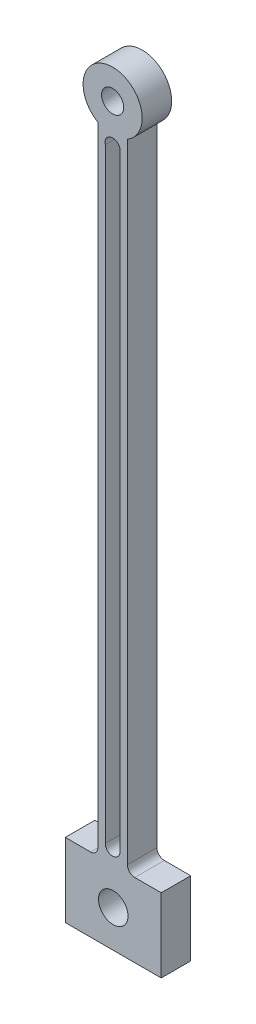
SolidWorks part; units mm, degrees
ref_plane "Front Plane" through (0, 0, 0) normal (0, 0, 1) x (1, 0, 0)
ref_plane "Top Plane" through (0, 0, 0) normal (0, 1, 0) x (1, 0, 0)
ref_plane "Right Plane" through (0, 0, 0) normal (1, 0, 0) x (0, 0, -1)
sketch "Sketch1" plane through (0, 0, 0) normal (0, 0, 1) x (1, 0, 0)
  line L0 (-6, -179.1632) -> (-12.837, -179.1632)
  line L2 (4, -6.9282) -> (4, -177.1632)
  line L4 (-4, -6.9282) -> (-4, -177.1632)
  line L5 (13.163, -179.1632) -> (6, -179.1632)
  line L6 (13.163, -179.1632) -> (13.163, -199.1632)
  line L7 (13.163, -199.1632) -> (-12.837, -199.1632)
  line L8 (-12.837, -179.1632) -> (-12.837, -199.1632)
  line L9 (13.163, -179.1632) -> (-12.837, -199.1632) construction
  line L10 (13.163, -199.1632) -> (-12.837, -179.1632) construction
  line L13 (-2, -11.1769) -> (-2, -175.1632)
  line L15 (2, -11.1769) -> (2, -175.1632)
  arc A0 (4, -6.9282) -> (-4, -6.9282) centre (0, 0) ccw
  circle A1 centre (0, 0) radius 5
  circle A2 centre (0, 0) radius 3
  circle A3 centre (0.163, -189.1632) radius 4
  circle A4 centre (0.163, -189.1632) radius 6
  arc A5 (-6, -179.1632) -> (-4, -177.1632) centre (-6, -177.1632) ccw
  arc A6 (6, -179.1632) -> (4, -177.1632) centre (6, -177.1632) cw
  arc A7 (2, -11.1769) -> (-2, -11.1769) centre (0, -10.6821) ccw
  arc A8 (-2, -175.1632) -> (2, -175.1632) centre (0, -175.1632) ccw
  point P17 (-4, -179.1632)
  point P28 (0, -177.1632)
  dimension "D1" = 16
  dimension "D2" = 10
  dimension "D3" = 6
  dimension "D5" = 26
  dimension "D7" = 12
  dimension "D8" = 8
  dimension "D4" = 2
  dimension "D12" = 166.4811
  dimension "D6" = 20
  dimension "D9" = 2
  dimension "D10" = 4
  dimension "D11" = 2
  dimension "D13" = 4
extrude "Boss-Extrude1" add sketch "Sketch1" along normal blind 8 contours L5 A6 L2 A0 L4 A5 L0 L8 L7 L6 A8 L13 A7 L15 A1 A4 | A1 A2 | A4 A3
